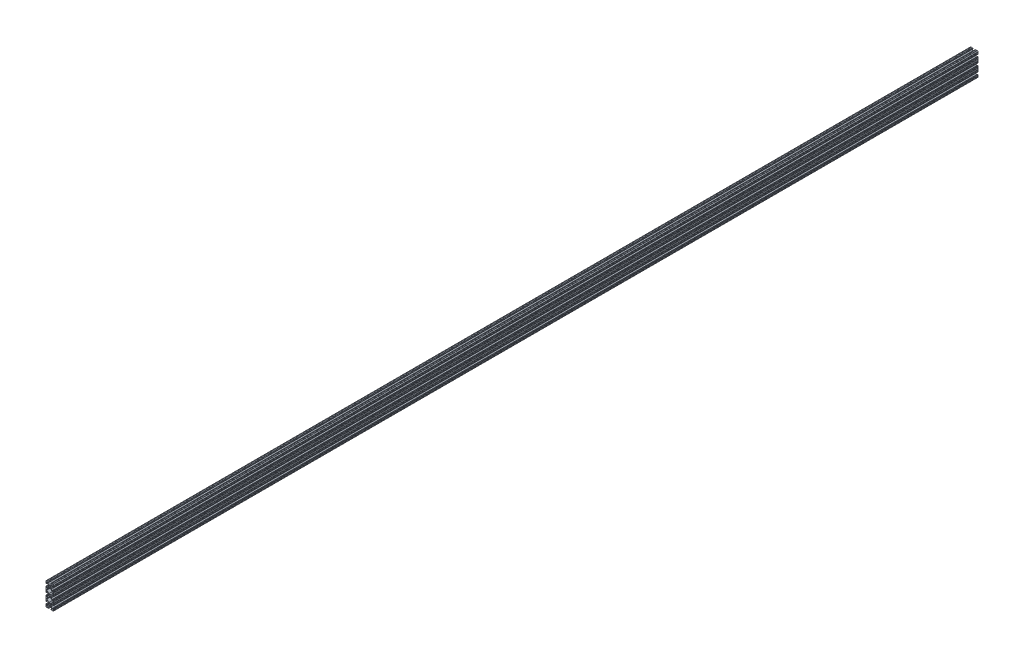
SolidWorks part; units mm, degrees
ref_plane "Front Plane" through (0, 0, 0) normal (0, 0, 1) x (1, 0, 0)
ref_plane "Top Plane" through (0, 0, 0) normal (0, 1, 0) x (1, 0, 0)
ref_plane "Right Plane" through (0, 0, 0) normal (1, 0, 0) x (0, 0, -1)
sketch "Sketch1" plane through (0, 0, 0) normal (0, 0, 1) x (1, 0, 0)
  line L0 (-12.7, 0) -> (12.7, 0) construction
  line L1 (-10.16, 13.1469) -> (-10.16, 12.2531)
  line L2 (-3.8143, 20.0397) -> (-9.7731, 14.0808)
  line L3 (0, 20.8915) -> (-1.7578, 20.8915)
  line L7 (-1.7578, 4.5085) -> (0, 4.5085)
  line L8 (-9.7731, 11.3192) -> (-3.8143, 5.3603)
  line L9 (-6.3246, 38.1) -> (-9.5504, 38.1)
  line L10 (-12.7, 34.8742) -> (-12.7, 31.7246)
  line L11 (-12.7, 30.7086) -> (-12.7, 29.7561)
  line L12 (-10.4902, 29.7561) -> (-10.4902, 31.7602)
  line L13 (-8.6864, 32.5073) -> (-5.3603, 29.1812)
  line L14 (-4.5085, 27.1248) -> (-4.5085, 23.6752)
  line L15 (-5.3603, 21.6188) -> (-8.6864, 18.2927)
  line L16 (-10.4902, 19.0398) -> (-10.4902, 21.0439)
  line L17 (-12.7, 21.0439) -> (-12.7, 20.0914)
  line L18 (-12.7, 19.0754) -> (-12.7, 15.8496)
  line L19 (-12.7, 14.8336) -> (-12.7, 10.5664)
  line L20 (-12.7, 9.5504) -> (-12.7, 6.3246)
  line L21 (-12.7, 5.3086) -> (-12.7, 4.3561)
  line L22 (-10.4902, 4.3561) -> (-10.4902, 6.3602)
  line L23 (-8.6864, 7.1073) -> (-5.3603, 3.7812)
  line L24 (-4.5085, 1.7248) -> (-4.5085, 0)
  line L25 (-11.5951, 28.6512) -> (-11.5951, 22.1488) construction
  line L26 (-11.5951, 25.4) -> (0, 25.4) construction
  line L27 (-12.7, 31.7246) -> (-6.3246, 38.1) construction
  line L28 (-12.7, 12.7) -> (0, 12.7) construction
  line L29 (-9.4336, 32.8168) -> (0, 32.8168) construction
  line L30 (-9.4336, 17.9832) -> (0, 17.9832) construction
  line L31 (-9.4336, 32.8168) -> (-9.4336, 17.9832) construction
  line L44 (0, 29.9085) -> (-1.7578, 29.9085)
  line L45 (-3.8143, 30.7603) -> (-7.1404, 34.0864)
  line L46 (-6.3932, 35.8902) -> (-4.3561, 35.8902)
  line L47 (-4.3561, 38.1) -> (-5.3086, 38.1)
  line L48 (0, 0) -> (0, 38.1) construction
  arc A0 (0, 28.0035) -> (0, 22.7965) centre (0, 25.4) ccw
  arc A1 (0, 2.6035) -> (-2.6035, 0) centre (0, 0) ccw
  arc A2 (-9.7731, 14.0808) -> (-10.16, 13.1469) centre (-8.8392, 13.1469) ccw
  arc A3 (-1.7578, 20.8915) -> (-3.8143, 20.0397) centre (-1.7578, 17.9832) ccw
  arc A8 (-3.8143, 5.3603) -> (-1.7578, 4.5085) centre (-1.7578, 7.4168) ccw
  arc A9 (-10.16, 12.2531) -> (-9.7731, 11.3192) centre (-8.8392, 12.2531) ccw
  arc A10 (-6.3246, 38.1) -> (-5.3086, 38.1) centre (-5.8166, 38.1) ccw
  arc A11 (-10.5664, 38.1) -> (-9.5504, 38.1) centre (-10.0584, 38.1) ccw
  arc A12 (-10.5664, 38.1) -> (-12.7, 35.8902) centre (-10.4888, 35.8902) ccw
  arc A13 (-12.7, 34.8742) -> (-12.7, 35.8902) centre (-12.7, 35.3822) ccw
  arc A14 (-12.7, 30.7086) -> (-12.7, 31.7246) centre (-12.7, 31.2166) ccw
  arc A15 (-12.7, 29.7561) -> (-10.4902, 29.7561) centre (-11.5951, 29.7561) ccw
  arc A16 (-8.6864, 32.5073) -> (-10.4902, 31.7602) centre (-9.4336, 31.7602) ccw
  arc A17 (-4.5085, 27.1248) -> (-5.3603, 29.1812) centre (-7.4168, 27.1248) ccw
  arc A18 (-5.3603, 21.6188) -> (-4.5085, 23.6752) centre (-7.4168, 23.6752) ccw
  arc A19 (-10.4902, 19.0398) -> (-8.6864, 18.2927) centre (-9.4336, 19.0398) ccw
  arc A20 (-10.4902, 21.0439) -> (-12.7, 21.0439) centre (-11.5951, 21.0439) ccw
  arc A21 (-12.7, 19.0754) -> (-12.7, 20.0914) centre (-12.7, 19.5834) ccw
  arc A22 (-12.7, 14.8336) -> (-12.7, 15.8496) centre (-12.7, 15.3416) ccw
  arc A23 (-12.7, 9.5504) -> (-12.7, 10.5664) centre (-12.7, 10.0584) ccw
  arc A24 (-12.7, 5.3086) -> (-12.7, 6.3246) centre (-12.7, 5.8166) ccw
  arc A25 (-12.7, 4.3561) -> (-10.4902, 4.3561) centre (-11.5951, 4.3561) ccw
  arc A26 (-8.6864, 7.1073) -> (-10.4902, 6.3602) centre (-9.4336, 6.3602) ccw
  arc A27 (-4.5085, 1.7248) -> (-5.3603, 3.7812) centre (-7.4168, 1.7248) ccw
  arc A49 (-3.8143, 30.7603) -> (-1.7578, 29.9085) centre (-1.7578, 32.8168) ccw
  arc A50 (-6.3932, 35.8902) -> (-7.1404, 34.0864) centre (-6.3932, 34.8336) ccw
  arc A51 (-4.3561, 35.8902) -> (-4.3561, 38.1) centre (-4.3561, 36.9951) ccw
  point P53 (-9.4336, 25.4)
  point P63 (-0.8789, 20.8915)
  dimension "D16" = 0.508
  dimension "D19" = 2.6035
  dimension "D27" = 1.0566
  dimension "D28" = 1.3208
  dimension "Rail Height" = 76.2
  dimension "Rail Width" = 25.4
  dimension "D3" = 2.2098
  dimension "D4" = 2.2098
  dimension "D5" = 2.2098
  dimension "D6" = 25.4
  dimension "D7" = 9.017
  dimension "D8" = 9.017
  dimension "TSlot Width" = 6.5024
  dimension "D9" = 2.2098
  dimension "D10" = 9.017
  dimension "D11" = 9.017
  dimension "D12" = 6.5024
  dimension "D13" = 6.5024
  dimension "D14" = 10.5664
  dimension "D15" = 5.3086
  dimension "D17" = 2.2098
  dimension "D18" = 16.383
  dimension "D2" = 45
  dimension "D20" = 45
  dimension "D21" = 45
  dimension "D22" = 2.54
  dimension "D23" = 25.4
  dimension "D24" = 4.2672
  dimension "D25" = 12.7508
  dimension "D26" = 14.8336
sketch "Sketch2" plane through (0, 0, 0) normal (1, 0, 0) x (0, 0, -1)
  line L0 (-1524, 0) -> (1524, 0)
  point P2 (-1460.5, 0)
  point P3 (1460.5, 0)
  dimension "Length" = 3048
  dimension "D1" = 63.5
  dimension "D2" = 63.5
sketch "Sketch3" plane through (0, 0, 0) normal (0, 0, 1) x (1, 0, 0)
  line L0 (-4.5085, 1.7248) -> (-4.5085, 0) construction
  line L1 (-8.6864, 7.1073) -> (-5.3603, 3.7812) construction
  line L2 (-10.4902, 4.3561) -> (-10.4902, 6.3602) construction
  line L3 (-12.7, 5.3086) -> (-12.7, 4.3561) construction
  line L4 (-12.7, 9.5504) -> (-12.7, 6.3246) construction
  line L5 (-12.7, 14.8336) -> (-12.7, 10.5664) construction
  line L6 (-12.7, 19.0754) -> (-12.7, 15.8496) construction
  line L7 (-12.7, 21.0439) -> (-12.7, 20.0914) construction
  line L8 (-10.4902, 19.0398) -> (-10.4902, 21.0439) construction
  line L9 (-5.3603, 21.6188) -> (-8.6864, 18.2927) construction
  line L10 (-4.5085, 27.1248) -> (-4.5085, 23.6752) construction
  line L11 (-8.6864, 32.5073) -> (-5.3603, 29.1812) construction
  line L12 (-10.4902, 29.7561) -> (-10.4902, 31.7602) construction
  line L13 (-12.7, 30.7086) -> (-12.7, 29.7561) construction
  line L14 (-12.7, 34.8742) -> (-12.7, 31.7246) construction
  line L15 (-6.3246, 38.1) -> (-9.5504, 38.1) construction
  line L16 (-4.3561, 38.1) -> (-5.3086, 38.1) construction
  line L17 (-6.3932, 35.8902) -> (-4.3561, 35.8902) construction
  line L18 (-3.8143, 30.7603) -> (-7.1404, 34.0864) construction
  line L19 (0, 29.9085) -> (-1.7578, 29.9085) construction
  line L20 (-1.7578, 4.5085) -> (0, 4.5085) construction
  line L21 (-9.7731, 11.3192) -> (-3.8143, 5.3603) construction
  line L22 (-10.16, 13.1469) -> (-10.16, 12.2531) construction
  line L23 (-3.8143, 20.0397) -> (-9.7731, 14.0808) construction
  line L24 (0, 20.8915) -> (-1.7578, 20.8915) construction
  line L25 (-4.5085, 1.7248) -> (-4.5085, 0)
  line L26 (-8.6864, 7.1073) -> (-5.3603, 3.7812)
  line L27 (-10.4902, 4.3561) -> (-10.4902, 6.3602)
  line L28 (-12.7, 5.3086) -> (-12.7, 4.3561)
  line L29 (-12.7, 9.5504) -> (-12.7, 6.3246)
  line L30 (-12.7, 14.8336) -> (-12.7, 10.5664)
  line L31 (-12.7, 19.0754) -> (-12.7, 15.8496)
  line L32 (-12.7, 21.0439) -> (-12.7, 20.0914)
  line L33 (-10.4902, 19.0398) -> (-10.4902, 21.0439)
  line L34 (-5.3603, 21.6188) -> (-8.6864, 18.2927)
  line L35 (-4.5085, 27.1248) -> (-4.5085, 23.6752)
  line L36 (-8.6864, 32.5073) -> (-5.3603, 29.1812)
  line L37 (-10.4902, 29.7561) -> (-10.4902, 31.7602)
  line L38 (-12.7, 30.7086) -> (-12.7, 29.7561)
  line L39 (-12.7, 34.8742) -> (-12.7, 31.7246)
  line L40 (-6.3246, 38.1) -> (-9.5504, 38.1)
  line L41 (-4.3561, 38.1) -> (-5.3086, 38.1)
  line L42 (-6.3932, 35.8902) -> (-4.3561, 35.8902)
  line L43 (-3.8143, 30.7603) -> (-7.1404, 34.0864)
  line L44 (0, 29.9085) -> (-1.7578, 29.9085)
  line L45 (-1.7578, 4.5085) -> (0, 4.5085)
  line L46 (-9.7731, 11.3192) -> (-3.8143, 5.3603)
  line L47 (-10.16, 13.1469) -> (-10.16, 12.2531)
  line L48 (-3.8143, 20.0397) -> (-9.7731, 14.0808)
  line L49 (0, 20.8915) -> (-1.7578, 20.8915)
  line L50 (0, 29.9085) -> (0, 28.0035)
  line L51 (0, 22.7965) -> (0, 20.8915)
  line L52 (0, 4.5085) -> (0, 2.6035)
  line L53 (-4.5085, 0) -> (-2.6035, 0)
  arc A0 (-4.5085, 1.7248) -> (-5.3603, 3.7812) centre (-7.4168, 1.7248) ccw construction
  arc A1 (-8.6864, 7.1073) -> (-10.4902, 6.3602) centre (-9.4336, 6.3602) ccw construction
  arc A2 (-12.7, 4.3561) -> (-10.4902, 4.3561) centre (-11.5951, 4.3561) ccw construction
  arc A3 (-12.7, 5.3086) -> (-12.7, 6.3246) centre (-12.7, 5.8166) ccw construction
  arc A4 (-12.7, 9.5504) -> (-12.7, 10.5664) centre (-12.7, 10.0584) ccw construction
  arc A5 (-12.7, 14.8336) -> (-12.7, 15.8496) centre (-12.7, 15.3416) ccw construction
  arc A6 (-12.7, 19.0754) -> (-12.7, 20.0914) centre (-12.7, 19.5834) ccw construction
  arc A7 (-10.4902, 21.0439) -> (-12.7, 21.0439) centre (-11.5951, 21.0439) ccw construction
  arc A8 (-10.4902, 19.0398) -> (-8.6864, 18.2927) centre (-9.4336, 19.0398) ccw construction
  arc A9 (-5.3603, 21.6188) -> (-4.5085, 23.6752) centre (-7.4168, 23.6752) ccw construction
  arc A10 (-4.5085, 27.1248) -> (-5.3603, 29.1812) centre (-7.4168, 27.1248) ccw construction
  arc A11 (-8.6864, 32.5073) -> (-10.4902, 31.7602) centre (-9.4336, 31.7602) ccw construction
  arc A12 (-12.7, 29.7561) -> (-10.4902, 29.7561) centre (-11.5951, 29.7561) ccw construction
  arc A13 (-12.7, 30.7086) -> (-12.7, 31.7246) centre (-12.7, 31.2166) ccw construction
  arc A14 (-12.7, 34.8742) -> (-12.7, 35.8902) centre (-12.7, 35.3822) ccw construction
  arc A15 (-10.5664, 38.1) -> (-12.7, 35.8902) centre (-10.4888, 35.8902) ccw construction
  arc A16 (-10.5664, 38.1) -> (-9.5504, 38.1) centre (-10.0584, 38.1) ccw construction
  arc A17 (-6.3246, 38.1) -> (-5.3086, 38.1) centre (-5.8166, 38.1) ccw construction
  arc A18 (-4.3561, 35.8902) -> (-4.3561, 38.1) centre (-4.3561, 36.9951) ccw construction
  arc A19 (-6.3932, 35.8902) -> (-7.1404, 34.0864) centre (-6.3932, 34.8336) ccw construction
  arc A20 (-3.8143, 30.7603) -> (-1.7578, 29.9085) centre (-1.7578, 32.8168) ccw construction
  arc A21 (-3.8143, 5.3603) -> (-1.7578, 4.5085) centre (-1.7578, 7.4168) ccw construction
  arc A22 (-10.16, 12.2531) -> (-9.7731, 11.3192) centre (-8.8392, 12.2531) ccw construction
  arc A23 (-9.7731, 14.0808) -> (-10.16, 13.1469) centre (-8.8392, 13.1469) ccw construction
  arc A24 (-1.7578, 20.8915) -> (-3.8143, 20.0397) centre (-1.7578, 17.9832) ccw construction
  arc A25 (0, 2.6035) -> (-2.6035, 0) centre (0, 0) ccw construction
  arc A26 (0, 28.0035) -> (0, 22.7965) centre (0, 25.4) ccw construction
  arc A27 (-4.5085, 1.7248) -> (-5.3603, 3.7812) centre (-7.4168, 1.7248) ccw
  arc A28 (-8.6864, 7.1073) -> (-10.4902, 6.3602) centre (-9.4336, 6.3602) ccw
  arc A29 (-12.7, 4.3561) -> (-10.4902, 4.3561) centre (-11.5951, 4.3561) ccw
  arc A30 (-12.7, 5.3086) -> (-12.7, 6.3246) centre (-12.7, 5.8166) ccw
  arc A31 (-12.7, 9.5504) -> (-12.7, 10.5664) centre (-12.7, 10.0584) ccw
  arc A32 (-12.7, 14.8336) -> (-12.7, 15.8496) centre (-12.7, 15.3416) ccw
  arc A33 (-12.7, 19.0754) -> (-12.7, 20.0914) centre (-12.7, 19.5834) ccw
  arc A34 (-10.4902, 21.0439) -> (-12.7, 21.0439) centre (-11.5951, 21.0439) ccw
  arc A35 (-10.4902, 19.0398) -> (-8.6864, 18.2927) centre (-9.4336, 19.0398) ccw
  arc A36 (-5.3603, 21.6188) -> (-4.5085, 23.6752) centre (-7.4168, 23.6752) ccw
  arc A37 (-4.5085, 27.1248) -> (-5.3603, 29.1812) centre (-7.4168, 27.1248) ccw
  arc A38 (-8.6864, 32.5073) -> (-10.4902, 31.7602) centre (-9.4336, 31.7602) ccw
  arc A39 (-12.7, 29.7561) -> (-10.4902, 29.7561) centre (-11.5951, 29.7561) ccw
  arc A40 (-12.7, 30.7086) -> (-12.7, 31.7246) centre (-12.7, 31.2166) ccw
  arc A41 (-12.7, 34.8742) -> (-12.7, 35.8902) centre (-12.7, 35.3822) ccw
  arc A42 (-10.5664, 38.1) -> (-12.7, 35.8902) centre (-10.4888, 35.8902) ccw
  arc A43 (-10.5664, 38.1) -> (-9.5504, 38.1) centre (-10.0584, 38.1) ccw
  arc A44 (-6.3246, 38.1) -> (-5.3086, 38.1) centre (-5.8166, 38.1) ccw
  arc A45 (-4.3561, 35.8902) -> (-4.3561, 38.1) centre (-4.3561, 36.9951) ccw
  arc A46 (-6.3932, 35.8902) -> (-7.1404, 34.0864) centre (-6.3932, 34.8336) ccw
  arc A47 (-3.8143, 30.7603) -> (-1.7578, 29.9085) centre (-1.7578, 32.8168) ccw
  arc A48 (-3.8143, 5.3603) -> (-1.7578, 4.5085) centre (-1.7578, 7.4168) ccw
  arc A49 (-10.16, 12.2531) -> (-9.7731, 11.3192) centre (-8.8392, 12.2531) ccw
  arc A50 (-9.7731, 14.0808) -> (-10.16, 13.1469) centre (-8.8392, 13.1469) ccw
  arc A51 (-1.7578, 20.8915) -> (-3.8143, 20.0397) centre (-1.7578, 17.9832) ccw
  arc A52 (0, 2.6035) -> (-2.6035, 0) centre (0, 0) ccw
  arc A53 (0, 28.0035) -> (0, 22.7965) centre (0, 25.4) ccw
extrude "Boss-Extrude1" add sketch "Sketch3" along normal mid plane 3048
mirror "Mirror1" about plane through (0, 0, 0) normal (1, 0, 0) of bodies 104
mirror "Mirror2" about plane through (0, 0, 0) normal (0, 1, 0) of bodies 105
equation "\"D3@Sketch1\" = \"Rail Width@Sketch1\" * 0.0870in"
equation "\"D4@Sketch1\"=\"D3@Sketch1\""
equation "\"D5@Sketch1\"=\"D3@Sketch1\""
equation "\"D6@Sketch1\" = \"Rail Width@Sketch1\""
equation "\"D7@Sketch1\" = \"Rail Width@Sketch1\" * 0.3550in"
equation "\"D8@Sketch1\"=\"D7@Sketch1\""
equation "\"D9@Sketch1\"=\"D4@Sketch1\""
equation "\"D10@Sketch1\"=\"D8@Sketch1\""
equation "\"D11@Sketch1\"=\"D7@Sketch1\""
equation "\"D12@Sketch1\"=\"TSlot Width@Sketch1\""
equation "\"D14@Sketch1\" = \"Rail Width@Sketch1\" * 0.4160in"
equation "\"D15@Sketch1\" = \"Rail Width@Sketch1\" * 0.2090in"
equation "\"D16@Sketch1\" = \"Rail Width@Sketch1\" * 0.0200in"
equation "\"D17@Sketch1\"=\"D9@Sketch1\""
equation "\"D18@Sketch1\" = \"Rail Width@Sketch1\" * 0.6450in"
equation "\"D19@Sketch1\" = \"Rail Width@Sketch1\" * 0.1025in"
equation "\"D22@Sketch1\"=\"Rail Width@Sketch1\"*0.10"
equation "\"D23@Sketch1\"=\"Rail Width@Sketch1\""
equation "\"D24@Sketch1\"=\"Rail Width@Sketch1\"*0.1680in"
equation "\"D25@Sketch1\"=\"Rail Width@Sketch1\"*0.5020in"
equation "\"D26@Sketch1\"=\"Rail Width@Sketch1\"*0.584"
equation "\"D27@Sketch1\"=\"Rail Width@Sketch1\"*0.0416in"
equation "\"D28@Sketch1\"=\"Rail Width@Sketch1\"*0.052"
equation "\"D1@Boss-Extrude1\"=\"length@sketch2\""
equation "\"D2@Sketch2\"=\"D1@Sketch2\""
equation "\"D13@Sketch1\"=\"TSlot Width@Sketch1\""
